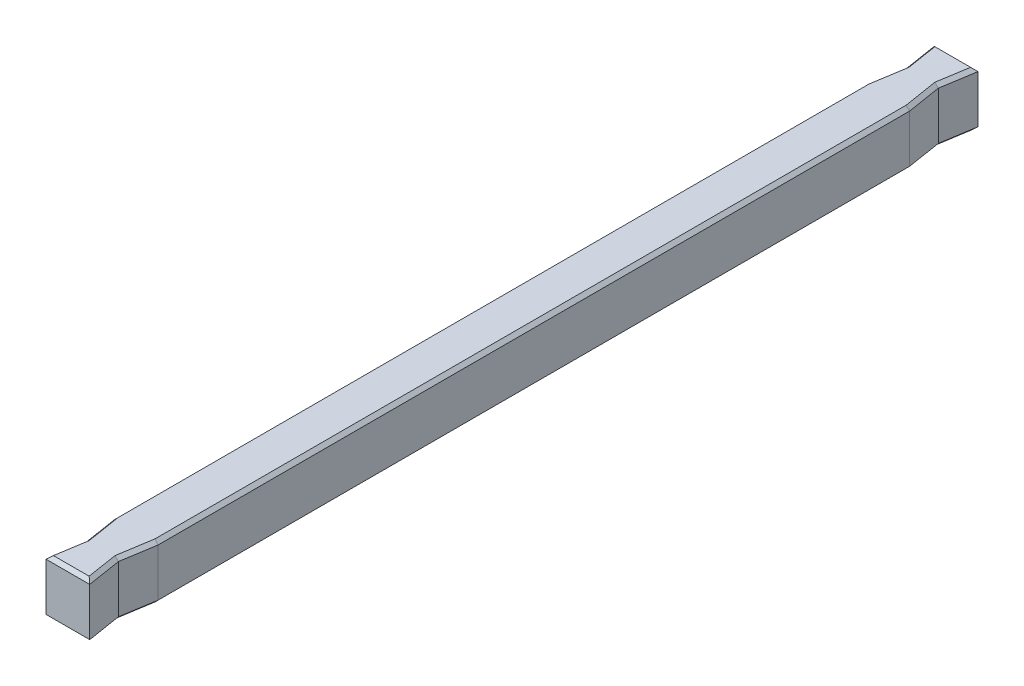
SolidWorks part; units mm, degrees
ref_plane "Front Plane" through (0, 0, 0) normal (0, 0, 1) x (1, 0, 0)
ref_plane "Top Plane" through (0, 0, 0) normal (0, 1, 0) x (1, 0, 0)
ref_plane "Right Plane" through (0, 0, 0) normal (1, 0, 0) x (0, 0, -1)
sketch "Sketch1" plane through (0, 0, 0) normal (0, 1, 0) x (1, 0, 0)
  line L0 (-1.6, 0) -> (1.6, 0)
  line L1 (-1.6, 0) -> (-1.2, 2.5)
  line L2 (-1.2, 2.5) -> (-1.6, 5)
  line L3 (-1.6, 5) -> (-1.6, 60)
  line L4 (-1.6, 60) -> (-1.2, 62.5)
  line L5 (-1.2, 62.5) -> (-1.6, 65)
  line L6 (-1.6, 65) -> (1.6, 65)
  line L7 (1.6, 65) -> (1.2, 62.5)
  line L8 (1.2, 62.5) -> (1.6, 60)
  line L9 (1.6, 60) -> (1.6, 5)
  line L10 (1.6, 5) -> (1.2, 2.5)
  line L11 (1.2, 2.5) -> (1.6, 0)
  line L12 (-1.2, 2.5) -> (1.2, 2.5) construction
  line L13 (-1.2, 62.5) -> (1.2, 62.5) construction
  dimension "D1" = 3.2
  dimension "D2" = 2.4
  dimension "D3" = 5
  dimension "D4" = 55
extrude "Boss-Extrude1" add sketch "Sketch1" along normal blind 4
chamfer "Chamfer1" distance 0.25 angle 45 24 edges at (0, 0, 0) (1.4, 0, -1.25) (1.4, 0, -3.75) (1.6, 0, -32.5) (1.4, 0, -61.25) (1.4, 0, -63.75) (0, 0, -65) (-1.4, 0, -63.75) (-1.4, 0, -61.25) (-1.6, 0, -32.5) (-1.4, 0, -3.75) (-1.4, 0, -1.25) (-1.4, 4, -3.75) (-1.6, 4, -32.5) (-1.4, 4, -61.25) (-1.4, 4, -63.75) (0, 4, -65) (1.4, 4, -63.75) (1.4, 4, -61.25) (1.6, 4, -32.5) (1.4, 4, -3.75) (1.4, 4, -1.25) (0, 4, 0) (-1.4, 4, -1.25)
